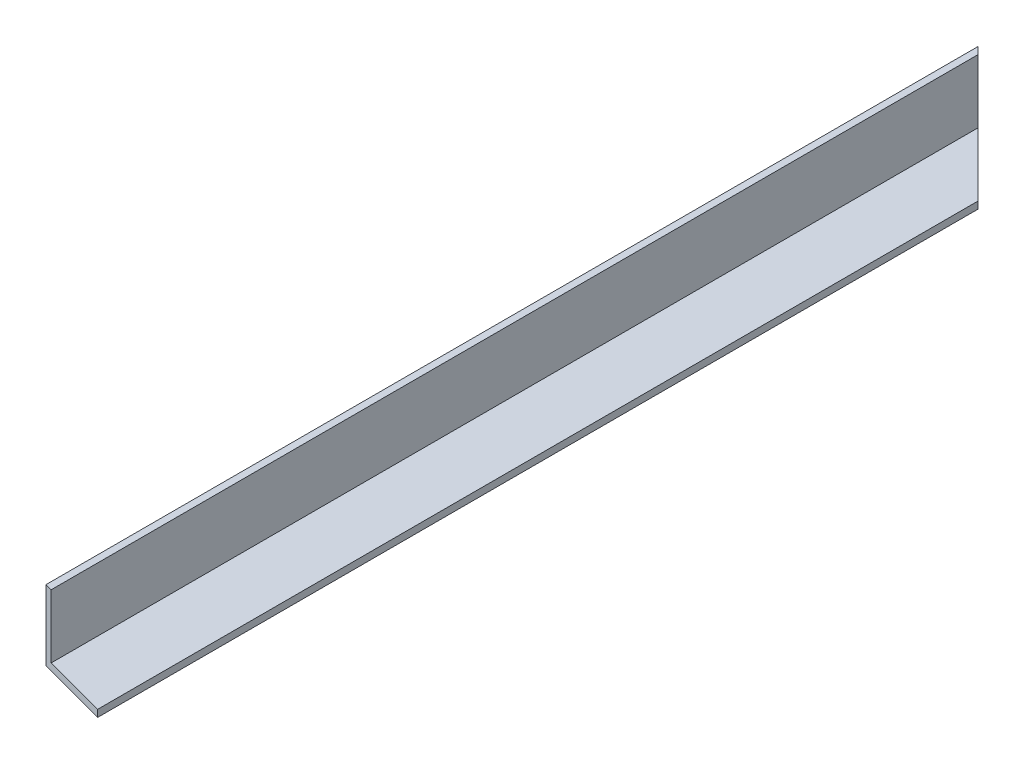
SolidWorks part; units mm, degrees
material "Acrylic (Medium-high impact)"
ref_plane "Front" through (0, 0, 0) normal (0, 0, 1) x (1, 0, 0)
ref_plane "Top" through (0, 0, 0) normal (0, 1, 0) x (1, 0, 0)
ref_plane "Right" through (0, 0, 0) normal (1, 0, 0) x (0, 0, -1)
sketch "Sketch1" plane through (0, 0, 0) normal (0, 0, 1) x (1, 0, 0)
  line L0 (0, 0) -> (0, 12.7)
  line L1 (0, 12.7) -> (1.27, 12.7)
  line L2 (1.27, 12.7) -> (1.27, 1.27)
  line L3 (1.27, 1.27) -> (12.7, 1.27)
  line L4 (12.7, 1.27) -> (12.7, 0)
  line L5 (12.7, 0) -> (0, 0)
  dimension "D1" = 12.7
  dimension "D2" = 11.43
extrude "Boss-Extrude1" add sketch "Sketch1" along normal blind 171.45
sketch "Sketch2" plane through (0, 1.27, 0) normal (0, 1, 0) x (1, 0, 0)
  line L7 (0, -168.047) -> (12.7, -171.45)
  line L8 (0, -171.45) -> (0, 0) construction
  line L9 (12.7, -171.45) -> (0, -171.45)
  line L10 (0, -171.45) -> (0, -168.047)
  line L11 (0, 0) -> (12.7, -12.7)
  line L12 (12.7, -171.45) -> (12.7, 0) construction
  line L13 (12.7, -12.7) -> (12.7, 0)
  line L14 (12.7, 0) -> (0, 0)
  dimension "D1" = 45
  dimension "D2" = 15
extrude "Cut-Extrude1" cut sketch "Sketch2" against normal through all and the other way through all
sketch "Sketch3" [suppressed] plane through (0, 1.27, 0) normal (0, 1, 0) x (1, 0, 0)
  line L0 (0, -203.2) -> (12.7, -190.5)
  line L1 (12.7, -203.2) -> (12.7, 0) construction
  line L2 (12.7, -190.5) -> (12.7, -203.2)
  line L3 (12.7, -203.2) -> (0, -203.2)
  line L4 (12.7, 0) -> (0, -3.403)
  line L5 (0, -203.2) -> (0, 0) construction
  line L6 (0, -3.403) -> (0, 0)
  line L7 (0, 0) -> (12.7, 0)
  dimension "D1" = 45
  dimension "D2" = 15
extrude "Cut-Extrude2" [suppressed] cut sketch "Sketch3" against normal through all and the other way through all
